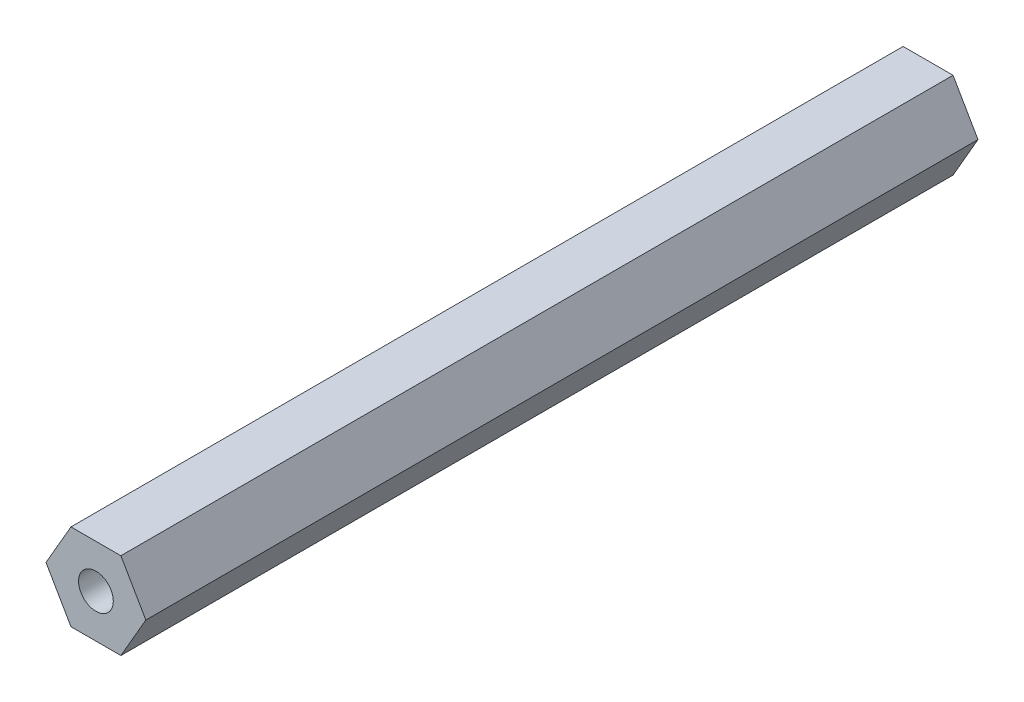
SolidWorks part; units mm, degrees
material "6061-T6 (SS)"
ref_plane "Front Plane" through (0, 0, 0) normal (0, 0, 1) x (1, 0, 0)
ref_plane "Top Plane" through (0, 0, 0) normal (0, 1, 0) x (1, 0, 0)
ref_plane "Right Plane" through (0, 0, 0) normal (1, 0, 0) x (0, 0, -1)
sketch "Sketch1" plane through (0, 0, 0) normal (0, 0, 1) x (1, 0, 0)
  line L1 (7.3323, 0) -> (3.6662, 6.35)
  line L2 (3.6662, 6.35) -> (-3.6662, 6.35)
  line L3 (-3.6662, 6.35) -> (-7.3323, 0)
  line L4 (-7.3323, 0) -> (-3.6662, -6.35)
  line L5 (-3.6662, -6.35) -> (3.6662, -6.35)
  line L6 (3.6662, -6.35) -> (7.3323, 0)
  circle A0 centre (0, 0) radius 6.35 construction
  circle A1 centre (0, 0) radius 2.5527
  dimension "D1" = 12.7
  dimension "D2" = 5.1054
extrude "Boss-Extrude1" add sketch "Sketch1" along normal blind 122.2375
